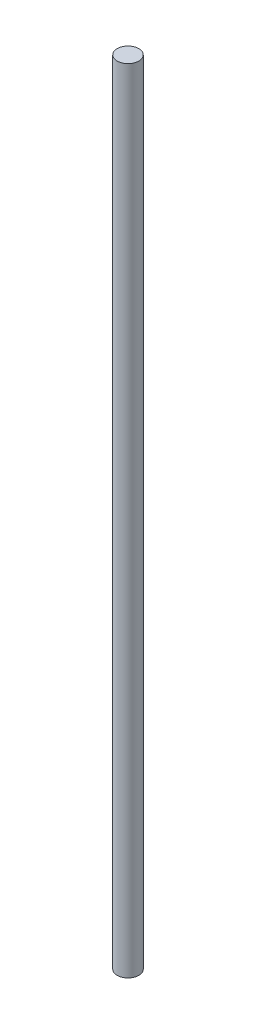
SolidWorks part; units mm, degrees
ref_plane "前视基准面" through (0, 0, 0) normal (0, 0, 1) x (1, 0, 0)
ref_plane "上视基准面" through (0, 0, 0) normal (0, 1, 0) x (1, 0, 0)
ref_plane "右视基准面" through (0, 0, 0) normal (1, 0, 0) x (0, 0, -1)
sketch "草图1" plane through (0, 0, 0) normal (0, 1, 0) x (1, 0, 0)
  circle A0 centre (0, 0) radius 1.5
  dimension "D1" = 3
extrude "凸台-拉伸1" add sketch "草图1" along normal blind 110
